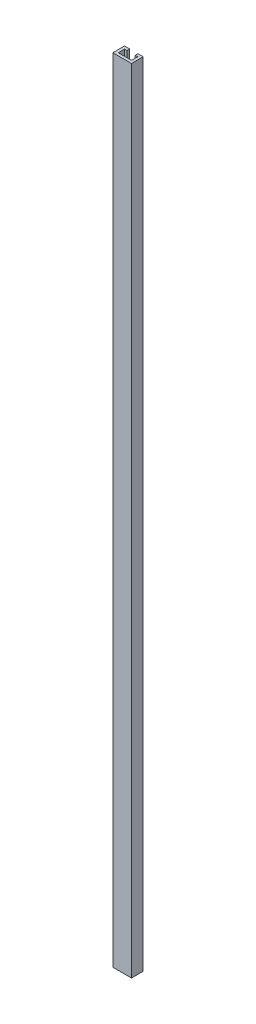
SolidWorks part; units mm, degrees
ref_plane "前视基准面" through (0, 0, 0) normal (0, 0, 1) x (1, 0, 0)
ref_plane "上视基准面" through (0, 0, 0) normal (0, 1, 0) x (1, 0, 0)
ref_plane "右视基准面" through (0, 0, 0) normal (1, 0, 0) x (0, 0, -1)
sketch "草图1" plane through (0, 0, 0) normal (0, 1, 0) x (1, 0, 0)
  line L0 (0, -5) -> (8, -5)
  line L1 (8, -5) -> (8, 0)
  line L2 (8, 0) -> (5.75, 0)
  line L3 (5.75, 0) -> (5.75, -1.15)
  line L4 (5.75, -1.15) -> (6.85, -1.15)
  line L5 (6.85, -1.15) -> (6.85, -3.85)
  line L6 (6.85, -3.85) -> (1.15, -3.85)
  line L7 (1.15, -3.85) -> (1.15, -1.15)
  line L8 (1.15, -1.15) -> (2.25, -1.15)
  line L9 (2.25, -1.15) -> (2.25, 0)
  line L10 (2.25, 0) -> (0, 0)
  line L11 (0, 0) -> (0, -5)
  line L12 (4, -3.85) -> (4, -5) construction
  line L13 (2.25, 0) -> (5.75, 0) construction
  line L14 (4, 0) -> (4, -3.85) construction
  dimension "D1" = 5
  dimension "D2" = 8
  dimension "D3" = 1.15
  dimension "D4" = 1.15
  dimension "D5" = 1.15
  dimension "D6" = 3.5
  dimension "D7" = 5.7
extrude "凸台-拉伸1" add sketch "草图1" along normal blind 340
